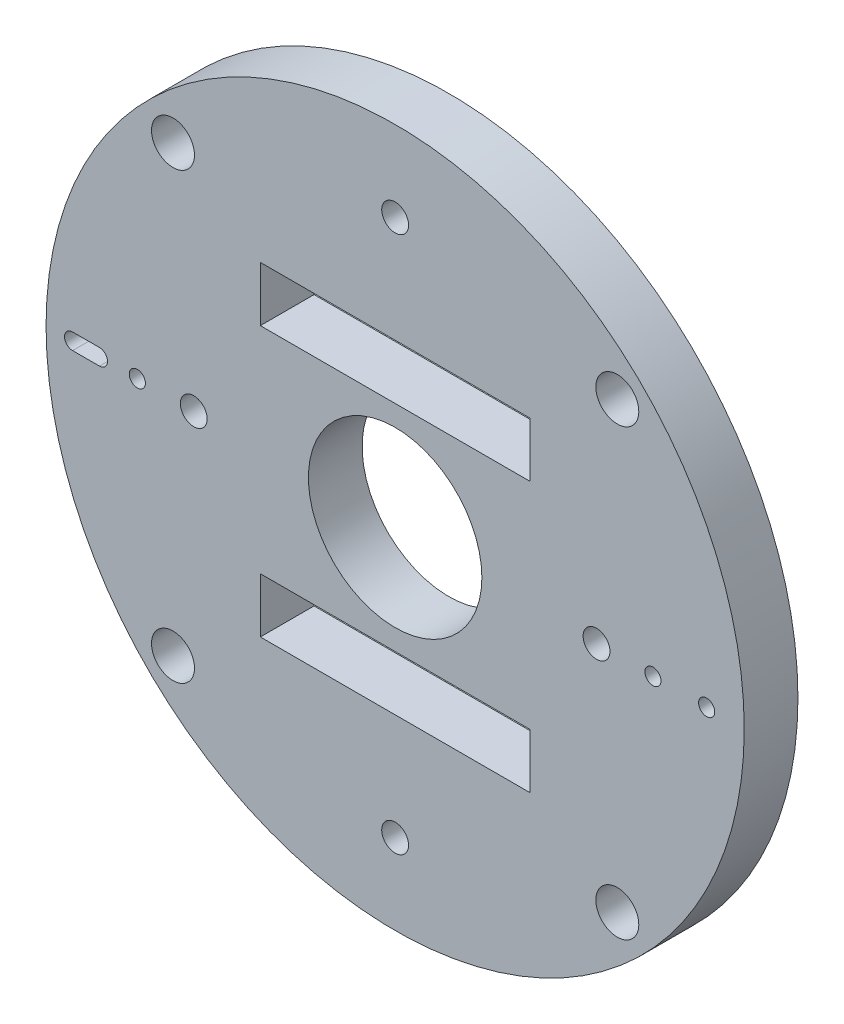
SolidWorks part; units mm, degrees
ref_plane "Front Plane" through (0, 0, 0) normal (0, 0, 1) x (1, 0, 0)
ref_plane "Top Plane" through (0, 0, 0) normal (0, 1, 0) x (1, 0, 0)
ref_plane "Right Plane" through (0, 0, 0) normal (1, 0, 0) x (0, 0, -1)
sketch "Sketch1" plane through (0, 0, 0) normal (0, 0, 1) x (1, 0, 0)
  line L31 (-25.1, -20) -> (25.1, -20)
  line L32 (-55.0566, 0) -> (-60.0566, 0) construction
  line L35 (-55.0566, -1.5) -> (-60.0566, -1.5)
  line L36 (-55.0566, 1.5) -> (-60.0566, 1.5)
  line L37 (25.1, -20) -> (25.1, -30.2)
  line L38 (25.1, -30.2) -> (-25.1, -30.2)
  line L39 (-25.1, -30.2) -> (-25.1, -20)
  line L40 (-25.1, 30.2) -> (25.1, 30.2)
  line L41 (-25.1, 30.2) -> (-25.1, 20)
  line L42 (-25.1, 20) -> (25.1, 20)
  line L43 (25.1, 20) -> (25.1, 30.2)
  circle A0 centre (0, 0) radius 65
  circle A1 centre (-37.5, 0) radius 2.5
  circle A2 centre (37.5, 0) radius 2.5
  circle A3 centre (0, 50) radius 2.5
  circle A4 centre (0, -50) radius 2.5
  circle A6 centre (0, 0) radius 16.15
  circle A12 centre (-41.3657, 41.3657) radius 4
  circle A13 centre (41.3657, -41.3657) radius 4
  circle A14 centre (41.3657, 41.3657) radius 4
  circle A15 centre (-41.3657, -41.3657) radius 4
  arc A25 (-55.0566, -1.5) -> (-55.0566, 1.5) centre (-55.0566, 0) ccw
  arc A26 (-60.0566, 1.5) -> (-60.0566, -1.5) centre (-60.0566, 0) ccw
  circle A27 centre (48, 0) radius 1.5
  circle A28 centre (58, 0) radius 1.5
  circle A29 centre (-48, 0) radius 1.5
  point P6 (0, 0)
  point P11 (0, 0)
  point P23 (29.6754, -19.9128)
  point P24 (0, -20)
  point P26 (0, 0)
  point P37 (0, 0)
  point P44 (-57.5566, 0)
  dimension "D1" = 130
extrude "Boss-Extrude1" add sketch "Sketch1" along normal blind 10
